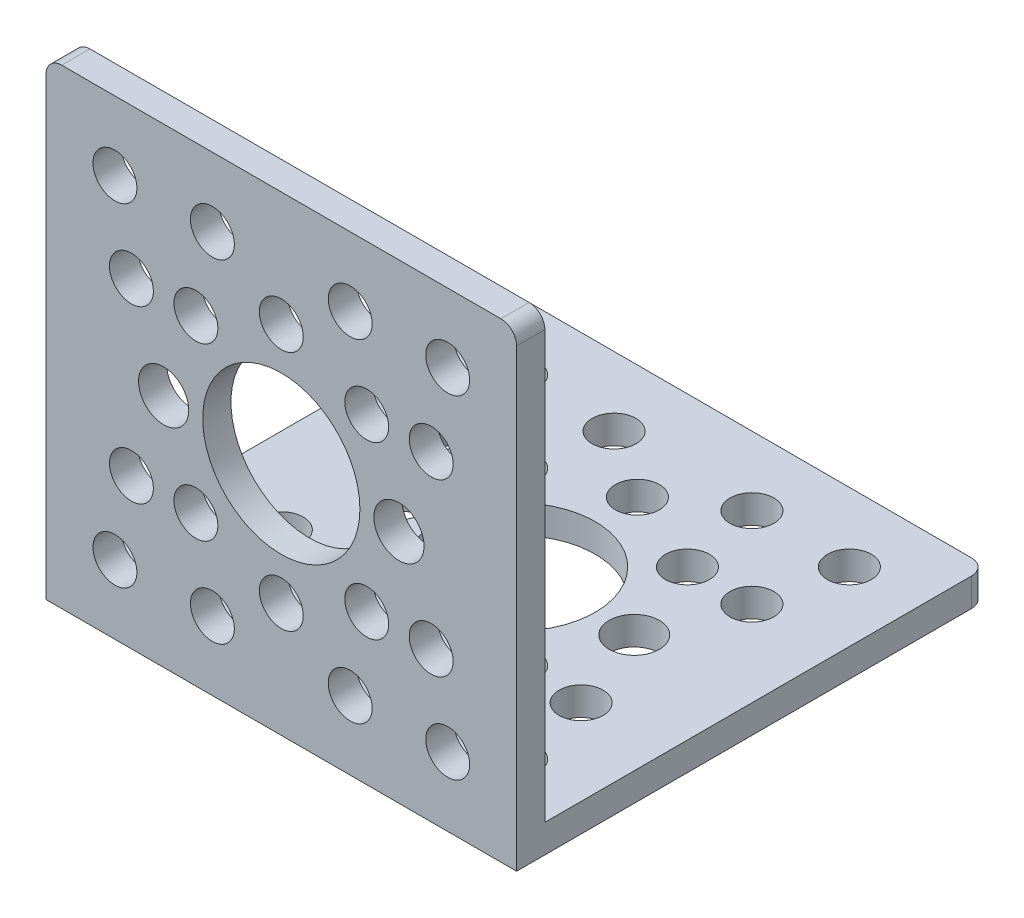
SolidWorks part; units mm, degrees
ref_plane "Front Plane" through (0, 0, 0) normal (0, 0, 1) x (1, 0, 0)
ref_plane "Top Plane" through (0, 0, 0) normal (0, 1, 0) x (1, 0, 0)
ref_plane "Right Plane" through (0, 0, 0) normal (1, 0, 0) x (0, 0, -1)
ref_plane "Plane1" through (0, 0, 0) normal (0, -1, 0) x (1, 0, 0)
sketch "Sketch1" plane through (0, 0, 0) normal (0, -1, 0) x (1, 0, 0)
  line L0 (-19.05, 19.05) -> (-19.05, -19.05)
  line L1 (-19.05, -19.05) -> (19.05, -19.05)
  line L2 (19.05, -19.05) -> (19.05, 19.05)
  line L3 (19.05, 19.05) -> (-19.05, 19.05)
extrude "Boss-Extrude1" add sketch "Sketch1" against normal blind 38.1
sketch "Sketch2" plane through (-19.05, 0, 0) normal (-1, 0, 0) x (0, 0, 1)
  line L0 (-19.05, 2.286) -> (16.764, 2.286)
  line L1 (16.764, 2.286) -> (16.764, 38.1)
  line L2 (16.764, 38.1) -> (-19.05, 38.1)
  line L3 (-19.05, 38.1) -> (-19.05, 2.286)
extrude "Cut-Extrude1" cut sketch "Sketch2" against normal through all
hole_wizard "Hole1" positions "Sketch4" profile "Sketch3" legacy
sketch "Sketch4" plane through (0, 0, 19.05) normal (0, 0, 1) x (1, 0, 0)
  point P0 (0, 19.05)
sketch "Sketch3" plane through (0, 19.05, 19.05) normal (1, 0, 0) x (0, -1, 0)
  line L0 (0, 0) -> (0, 38.1)
  line L1 (0, 38.1) -> (6.3627, 38.1)
  line L2 (6.3627, 38.1) -> (6.3627, 0)
  line L3 (6.3627, 0) -> (0, 0)
  line L4 (0, 110) -> (0, -10) construction
  dimension "Diameter" = 12.7254
  dimension "Depth" = 38.1
hole_wizard "M3.5 Clearance Hole1" positions "Sketch6" profile "Sketch5" hole size "M3.5" standard "ANSI Metric"
sketch "Sketch6" plane through (0, 0, 19.05) normal (0, 0, 1) x (1, 0, 0)
  point P0 (-9.525, 19.05)
  point P1 (9.525, 19.05)
sketch "Sketch5" plane through (-9.525, 19.05, 19.05) normal (1, 0, 0) x (0, -1, 0)
  line L0 (0, 0) -> (0, 38.1)
  line L1 (0, 38.1) -> (2.032, 38.1)
  line L2 (2.032, 38.1) -> (2.032, 0)
  line L5 (2.032, 0) -> (0, 0)
  line L11 (0, -6.35) -> (0, 107.95) construction
  dimension "Thru Hole Dia." = 4.064
  dimension "Thru Hole Depth" = 38.1
hole_wizard "M3 Clearance Hole1" positions "Sketch8" profile "Sketch7" hole size "M3" standard "ANSI Metric"
sketch "Sketch8" plane through (0, 0, 19.05) normal (0, 0, 1) x (1, 0, 0)
  point P0 (12.1352, 12.1352)
  point P1 (-5.5796, 32.5204)
  point P2 (-12.1352, 25.9648)
  point P3 (5.5796, 32.5204)
  point P4 (12.1352, 25.9648)
  point P5 (13.4704, 32.5204)
  point P6 (-13.4704, 5.5796)
  point P7 (-13.4704, 32.5204)
  point P8 (13.4704, 5.5796)
  point P9 (6.9148, 25.9648)
  point P10 (6.9148, 12.1352)
  point P11 (0, 9.271)
  point P12 (-6.9148, 12.1352)
  point P13 (-6.9148, 25.9648)
  point P14 (0, 28.829)
  point P15 (-12.1352, 12.1352)
  point P16 (-5.5796, 5.5796)
  point P17 (5.5796, 5.5796)
sketch "Sketch7" plane through (12.1352, 12.1352, 19.05) normal (1, 0, 0) x (0, -1, 0)
  line L0 (0, 0) -> (0, 38.1)
  line L1 (0, 38.1) -> (1.778, 38.1)
  line L2 (1.778, 38.1) -> (1.778, 0)
  line L5 (1.778, 0) -> (0, 0)
  line L11 (0, -6.35) -> (0, 107.95) construction
  dimension "Thru Hole Dia." = 3.556
  dimension "Thru Hole Depth" = 38.1
hole_wizard "Hole2" positions "Sketch10" profile "Sketch9" legacy
sketch "Sketch10" plane through (0, 2.286, 0) normal (0, 1, 0) x (1, 0, 0)
  point P0 (0, 0)
sketch "Sketch9" plane through (0, 2.286, 0) normal (1, 0, 0) x (0, 0, 1)
  line L0 (0, 0) -> (0, 2.286)
  line L1 (0, 2.286) -> (6.3627, 2.286)
  line L2 (6.3627, 2.286) -> (6.3627, 0)
  line L3 (6.3627, 0) -> (0, 0)
  line L4 (0, 110) -> (0, -10) construction
  dimension "Diameter" = 12.7254
  dimension "Depth" = 2.286
hole_wizard "M3.5 Clearance Hole2" positions "Sketch12" profile "Sketch11" hole size "M3.5" standard "ANSI Metric"
sketch "Sketch12" plane through (0, 2.286, 0) normal (0, 1, 0) x (1, 0, 0)
  point P0 (-9.525, 0)
  point P1 (9.525, 0)
sketch "Sketch11" plane through (-9.525, 2.286, 0) normal (1, 0, 0) x (0, 0, 1)
  line L0 (0, 0) -> (0, 2.286)
  line L1 (0, 2.286) -> (2.032, 2.286)
  line L2 (2.032, 2.286) -> (2.032, 0)
  line L5 (2.032, 0) -> (0, 0)
  line L11 (0, -6.35) -> (0, 107.95) construction
  dimension "Thru Hole Dia." = 4.064
  dimension "Thru Hole Depth" = 2.286
hole_wizard "M3 Clearance Hole2" positions "Sketch14" profile "Sketch13" hole size "M3" standard "ANSI Metric"
sketch "Sketch14" plane through (0, 2.286, 0) normal (0, 1, 0) x (1, 0, 0)
  point P0 (5.5796, -13.4704)
  point P1 (12.1352, -6.9148)
  point P2 (-5.5796, -13.4704)
  point P3 (-12.1352, -6.9148)
  point P4 (-5.5796, 13.4704)
  point P5 (-12.1352, 6.9148)
  point P6 (5.5796, 13.4704)
  point P7 (12.1352, 6.9148)
  point P8 (-13.4704, 13.4704)
  point P9 (13.4704, -13.4704)
  point P10 (13.4704, 13.4704)
  point P11 (-13.4704, -13.4704)
  point P12 (-6.9148, 6.9148)
  point P13 (-6.9148, -6.9148)
  point P14 (0, -9.779)
  point P15 (6.9148, -6.9148)
  point P16 (6.9148, 6.9148)
  point P17 (0, 9.779)
sketch "Sketch13" plane through (5.5796, 2.286, 13.4704) normal (1, 0, 0) x (0, 0, 1)
  line L0 (0, 0) -> (0, 2.286)
  line L1 (0, 2.286) -> (1.778, 2.286)
  line L2 (1.778, 2.286) -> (1.778, 0)
  line L5 (1.778, 0) -> (0, 0)
  line L11 (0, -6.35) -> (0, 107.95) construction
  dimension "Thru Hole Dia." = 3.556
  dimension "Thru Hole Depth" = 2.286
fillet "Fillet1" radius 1.27 4 edges at (-19.05, 38.1, 17.907) (19.05, 38.1, 17.907) (19.05, 1.143, -19.05) (-19.05, 1.143, -19.05)
